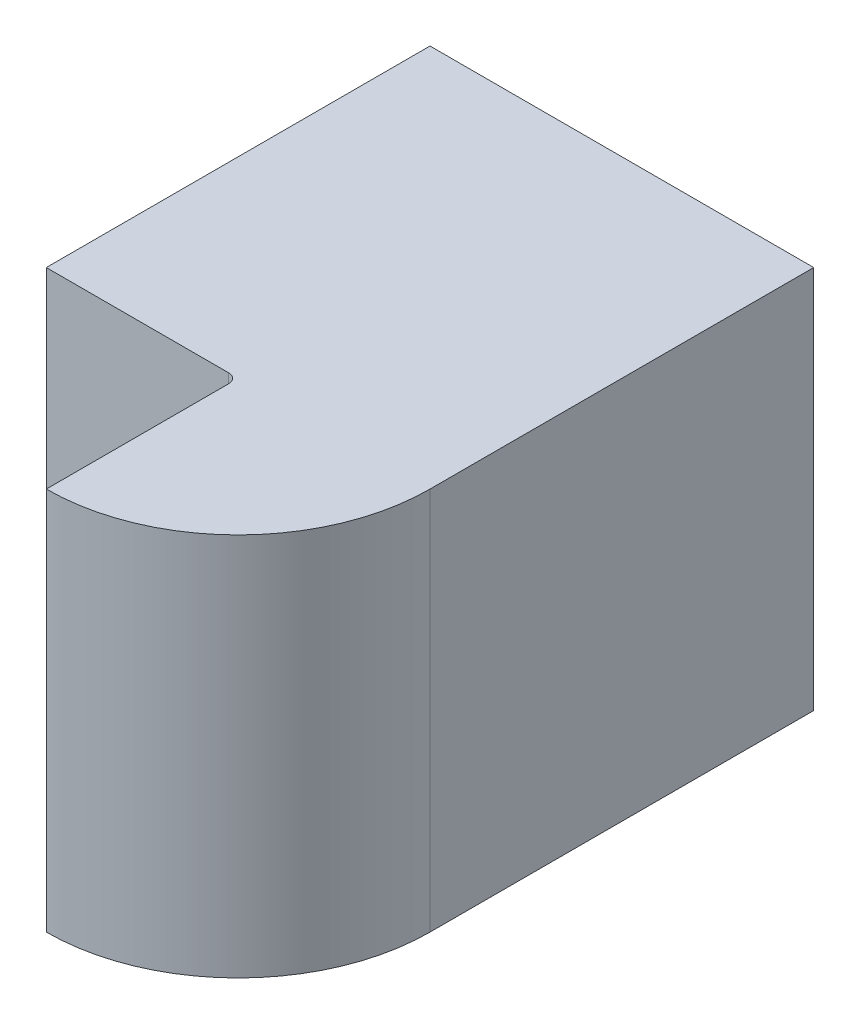
SolidWorks part; units mm, degrees
ref_plane "Front Plane" through (0, 0, 0) normal (0, 0, 1) x (1, 0, 0)
ref_plane "Top Plane" through (0, 0, 0) normal (0, 1, 0) x (1, 0, 0)
ref_plane "Right Plane" through (0, 0, 0) normal (1, 0, 0) x (0, 0, -1)
sketch "Sketch1" plane through (0, 0, 0) normal (0, 1, 0) x (1, 0, 0)
  line L1 (-50.8, -50.8) -> (50.8, -50.8)
  line L2 (-50.8, -50.8) -> (-50.8, 50.8)
  line L3 (-50.8, 50.8) -> (50.8, 50.8)
  line L4 (50.8, -50.8) -> (50.8, 50.8)
  line L5 (-50.8, -50.8) -> (50.8, 50.8) construction
  line L6 (-50.8, 50.8) -> (50.8, -50.8) construction
  point P0 (0, 0)
  dimension "D1" = 101.6
  dimension "D2" = 101.6
extrude "Boss-Extrude1" add sketch "Sketch1" along normal blind 101.6 contours L1 L4 L3 L2
sketch "Sketch3" plane through (0, 0, 50.8) normal (0, 0, 1) x (1, 0, 0)
  line L0 (0, 0) -> (0, 101.6)
  line L1 (-50.8, 101.6) -> (50.8, 101.6) construction
  line L2 (0, 101.6) -> (50.8, 101.6)
  line L3 (50.8, 101.6) -> (50.8, 0)
  line L4 (50.8, 0) -> (0, 0)
revolve "Revolve1" add sketch "Sketch3" angle 90 about L0
fillet "Fillet1" radius 2.54 1 edges at (0, 50.8, 50.8)
